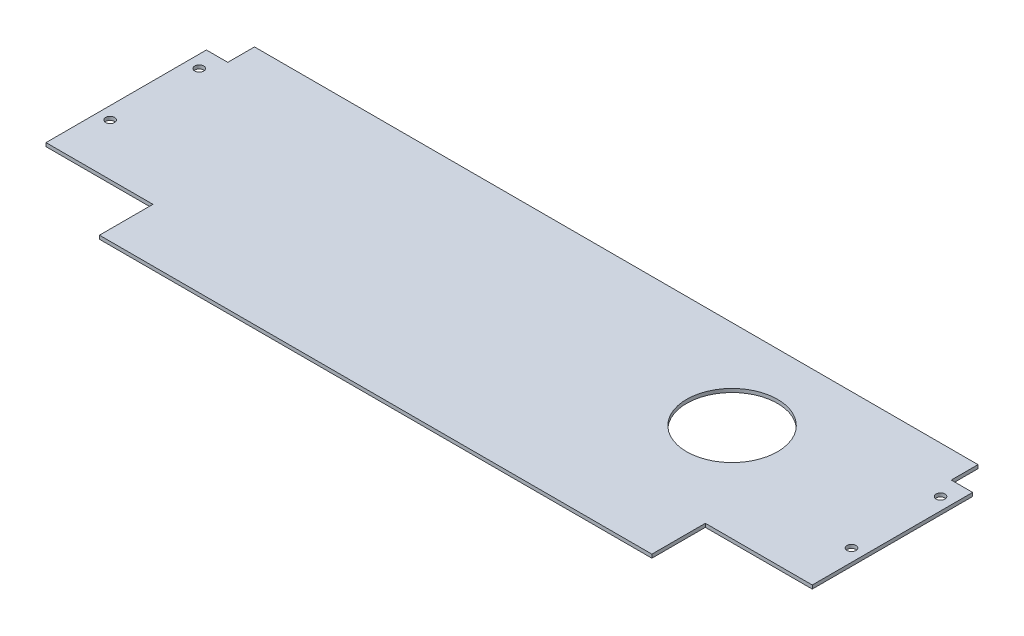
SolidWorks part; units mm, degrees
material "1060 Сплав"
ref_plane "Front" through (0, 0, 0) normal (0, 0, 1) x (1, 0, 0)
ref_plane "Top" through (0, 0, 0) normal (0, 1, 0) x (1, 0, 0)
ref_plane "Right" through (0, 0, 0) normal (1, 0, 0) x (0, 0, -1)
sketch "Эскиз2" plane through (0, 0, 0) normal (0, 1, 0) x (1, 0, 0)
  line L1 (0, 0) -> (430, 0)
  line L2 (0, 0) -> (0, 135)
  line L3 (0, 135) -> (430, 135)
  line L4 (430, 0) -> (430, 135)
  dimension "D1" = 430
  dimension "D2" = 135
extrude "Бобышка-Вытянуть1" add sketch "Эскиз2" along normal blind 2
sketch "Эскиз3" plane through (0, 2, 0) normal (0, 1, 0) x (1, 0, 0)
  line L0 (0, 135) -> (0, 0) construction
  line L1 (430, 135) -> (0, 135) construction
  line L2 (215, 135) -> (215, 0) construction
  line L3 (418, 135) -> (418, 120)
  line L4 (0, 135) -> (12, 135)
  line L5 (0, 135) -> (0, 120)
  line L6 (0, 120) -> (12, 120)
  line L7 (12, 135) -> (12, 120)
  line L8 (430, 120) -> (418, 120)
  line L9 (430, 135) -> (430, 120)
  line L10 (430, 135) -> (418, 135)
  line L11 (0, 0) -> (430, 0) construction
  line L12 (370, 0) -> (370, 30)
  line L13 (0, 0) -> (60, 0)
  line L14 (0, 0) -> (0, 30)
  line L15 (0, 30) -> (60, 30)
  line L16 (60, 0) -> (60, 30)
  line L17 (430, 30) -> (370, 30)
  line L18 (430, 0) -> (430, 30)
  line L19 (430, 0) -> (370, 0)
  circle A0 centre (7, 109) radius 2.5
  circle A1 centre (423, 109) radius 2.5
  circle A2 centre (7, 59) radius 2.5
  circle A3 centre (423, 59) radius 2.5
  dimension "D1" = 5
  dimension "D2" = 7
  dimension "D3" = 26
  dimension "D4" = 12
  dimension "D5" = 15
  dimension "D6" = 30
  dimension "D7" = 60
  dimension "D8" = 2
extrude "Вырез-Вытянуть1" cut sketch "Эскиз3" against normal through all
sketch "Эскиз4" plane through (0, 2, 0) normal (0, 1, 0) x (1, 0, 0)
  line L0 (418, 135) -> (12, 135) construction
  line L2 (430, 30) -> (430, 120) construction
  circle A0 centre (330, 85) radius 25.5
  dimension "D1" = 50
  dimension "D2" = 100
  dimension "D3" = 51
extrude "Вырез-Вытянуть2" cut sketch "Эскиз4" against normal through all
